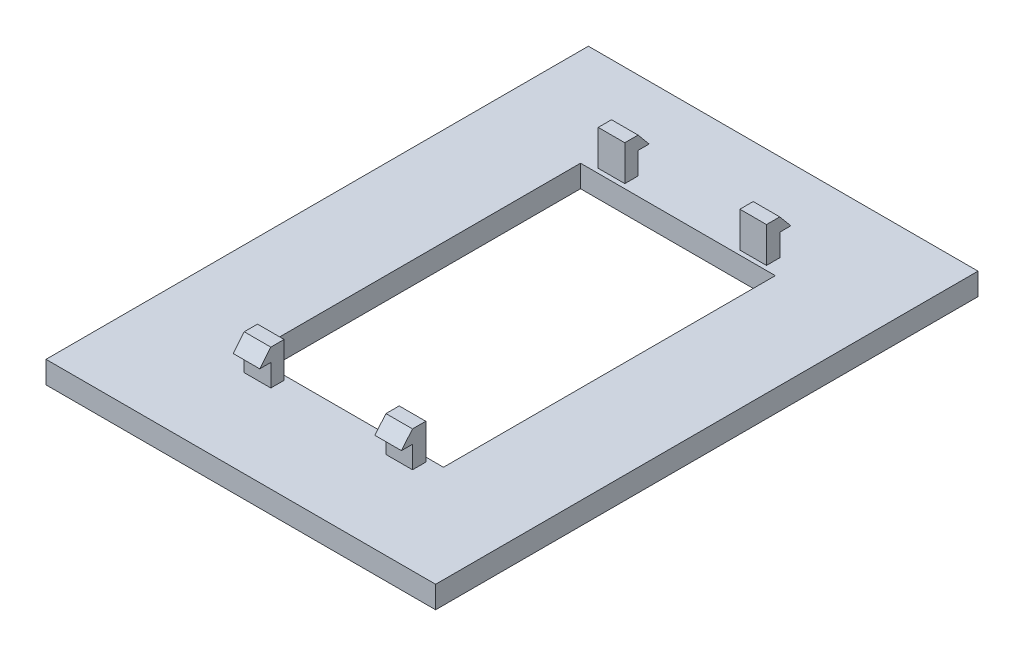
SolidWorks part; units mm, degrees
material "ABS"
ref_plane "Alzado" through (0, 0, 0) normal (0, 0, 1) x (1, 0, 0)
ref_plane "Planta" through (0, 0, 0) normal (0, 1, 0) x (1, 0, 0)
ref_plane "Vista lateral" through (0, 0, 0) normal (1, 0, 0) x (0, 0, -1)
sketch "Croquis1" plane through (0, 0, 0) normal (0, 1, 0) x (1, 0, 0)
  line L1 (-44, 61.25) -> (44, 61.25)
  line L2 (-44, 61.25) -> (-44, -61.25)
  line L3 (-44, -61.25) -> (44, -61.25)
  line L4 (44, 61.25) -> (44, -61.25)
  line L5 (-44, 61.25) -> (44, -61.25) construction
  line L6 (-44, -61.25) -> (44, 61.25) construction
  point P0 (0, 0)
  dimension "D1" = 122.5
  dimension "D2" = 88
extrude "Saliente-Extruir1" add sketch "Croquis1" along normal blind 5
sketch "Croquis2" plane through (0, 5, 0) normal (0, 1, 0) x (1, 0, 0)
  line L1 (-22, 37.475) -> (22, 37.475)
  line L2 (-22, 37.475) -> (-22, -37.475)
  line L3 (-22, -37.475) -> (22, -37.475)
  line L4 (22, 37.475) -> (22, -37.475)
  line L5 (-22, 37.475) -> (22, -37.475) construction
  line L6 (-22, -37.475) -> (22, 37.475) construction
  point P0 (0, 0)
  dimension "D1" = 74.95
  dimension "D2" = 44
extrude "Cortar-Extruir1" cut sketch "Croquis2" against normal blind 5
sketch "Croquis3" plane through (0, 5, 0) normal (0, 1, 0) x (1, 0, 0)
  line L0 (0, 37.475) -> (-16, 37.475)
  line L1 (22, 37.475) -> (-22, 37.475) construction
  line L2 (-16, 37.475) -> (-16, 41.475)
  line L3 (-16, 41.475) -> (-13, 41.475)
  line L4 (-13, 41.475) -> (-13, 38.475)
  line L5 (-13, 38.475) -> (-19, 38.475)
  line L6 (-19, 38.475) -> (-19, 41.475)
  line L7 (-19, 41.475) -> (-16, 41.475)
  line L8 (0, 37.475) -> (0, 28.4634)
  line L9 (0, 0) -> (-11.4122, 0)
  line L10 (19, 41.475) -> (16, 41.475)
  line L11 (19, 38.475) -> (19, 41.475)
  line L12 (13, 38.475) -> (19, 38.475)
  line L13 (13, 41.475) -> (13, 38.475)
  line L14 (16, 41.475) -> (13, 41.475)
  line L15 (16, 37.475) -> (16, 41.475)
  line L16 (-19, -38.475) -> (-19, -41.475)
  line L17 (-13, -38.475) -> (-19, -38.475)
  line L18 (19, -38.475) -> (19, -41.475)
  line L19 (19, -41.475) -> (16, -41.475)
  line L20 (16, -37.475) -> (16, -41.475)
  line L21 (16, -41.475) -> (13, -41.475)
  line L22 (13, -41.475) -> (13, -38.475)
  line L23 (13, -38.475) -> (19, -38.475)
  line L24 (-19, -41.475) -> (-16, -41.475)
  line L25 (-13, -41.475) -> (-13, -38.475)
  line L26 (-16, -41.475) -> (-13, -41.475)
  line L27 (-16, -37.475) -> (-16, -41.475)
  line L28 (0, -37.475) -> (-16, -37.475)
  dimension "D1" = 1
  dimension "D2" = 3
extrude "Saliente-Extruir7" add sketch "Croquis3" along normal blind 8 contours L5 L4 L3 L2 | L7 L6 L5 L2 | L15 L12 L11 L10 | L12 L15 L14 L13 | L17 L27 L26 L25 | L27 L17 L16 L24 | L23 L20 L19 L18 | L23 L22 L21 L20
sketch "Croquis5" plane through (-19, 0, 0) normal (-1, 0, 0) x (0, 0, 1)
  line L0 (41.475, 13) -> (41.475, 10)
  line L1 (41.475, 13) -> (41.475, 5) construction
  line L2 (41.475, 10) -> (43.975, 10)
  line L3 (43.975, 10) -> (41.475, 13)
  line L4 (0, 0) -> (0, 15.9234)
  line L5 (-43.975, 10) -> (-41.475, 13)
  line L6 (-41.475, 10) -> (-43.975, 10)
  line L7 (-41.475, 13) -> (-41.475, 10)
  line M2 (41.475, 5) -> (41.475, 13)
extrude "Saliente-Extruir8" add sketch "Croquis5" against normal blind 38 contours L7 L5 L6 | L2 L3 M2
sketch "Croquis6" plane through (0, 5, 0) normal (0, 1, 0) x (1, 0, 0)
  line L0 (19, 43.975) -> (-19, 43.975) construction
  line L1 (-13, 43.975) -> (13, 43.975)
  line L2 (-13, 43.975) -> (-13, -43.975)
  line L3 (-13, -43.975) -> (13, -43.975)
  line L4 (13, 43.975) -> (13, -43.975)
  line L5 (19, -43.975) -> (-19, -43.975) construction
extrude "Cortar-Extruir3" cut sketch "Croquis6" along normal blind 19
